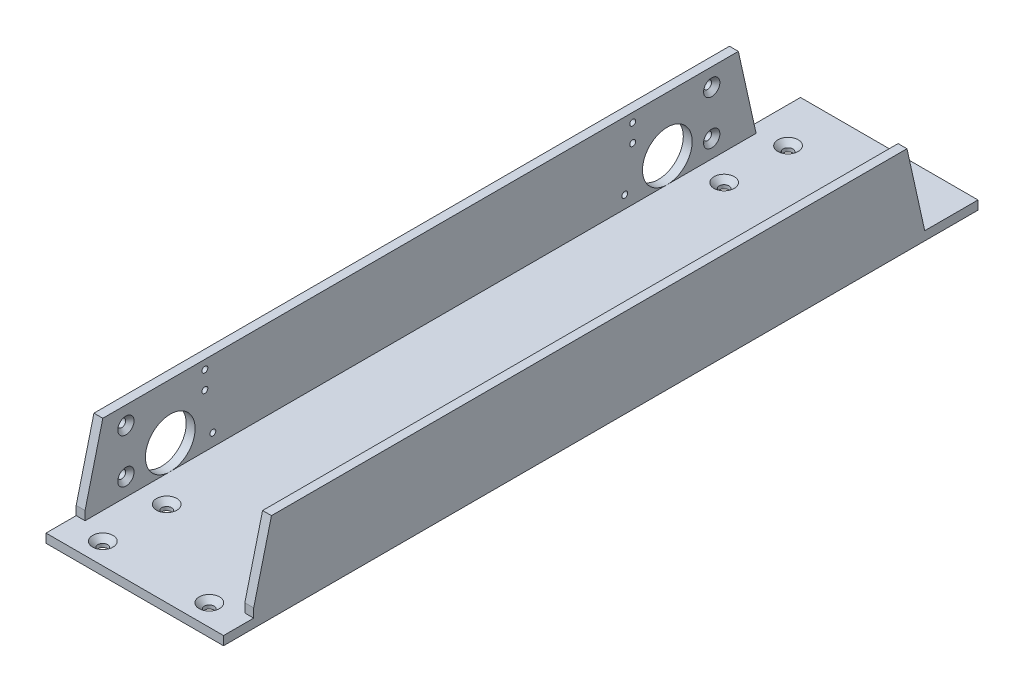
SolidWorks part; units mm, degrees
material "Д16Т ГОСТ 4784-74"
ref_plane "Спереди" through (0, 0, 0) normal (0, 0, 1) x (1, 0, 0)
ref_plane "Сверху" through (0, 0, 0) normal (0, 1, 0) x (1, 0, 0)
ref_plane "Справа" through (0, 0, 0) normal (1, 0, 0) x (0, 0, -1)
sketch "Эскиз1" plane through (0, 0, 0) normal (0, 0, 1) x (1, 0, 0)
  line L0 (0, 0) -> (0, 50)
  line L1 (0, 50) -> (5, 50)
  line L2 (5, 50) -> (5, 5)
  line L3 (5, 5) -> (95, 5)
  line L4 (95, 5) -> (95, 50)
  line L5 (95, 50) -> (100, 50)
  line L6 (100, 50) -> (100, 0)
  line L7 (100, 0) -> (0, 0)
  line L8 (5, 5) -> (5, 0) construction
  dimension "D1" = 100
  dimension "D2" = 50
  dimension "D3" = 5
extrude "Бобышка-Вытянуть1" add sketch "Эскиз1" along normal blind 400
hole_wizard "Зенковка для винта с потайной головкой и внутренним шестигранником M51" positions "Эскиз10" profile "Эскиз9" countersink size "M5" standard "DIN" end condition through all
sketch "Эскиз10" plane through (0, 5, 0) normal (0, 1, 0) x (-1, 0, 0)
  line L0 (-50, 400) -> (-50, 252.8897) construction
  line L1 (-95, 400) -> (-5, 400) construction
  line L3 (-10.9061, 375) -> (-70.1263, 375) construction
  line L4 (-5, 200) -> (-80, 200) construction
  line L5 (-5, 400) -> (-5, 0) construction
  line L7 (-10.9061, 25) -> (-70.1263, 25) construction
  line L8 (-50, 0) -> (-50, 147.1103) construction
  point P0 (-80, 393)
  point P1 (-20, 393)
  point P3 (-20, 357)
  point P5 (-80, 357)
  point P32 (-80, 43)
  point P33 (-20, 43)
  point P34 (-20, 7)
  point P35 (-80, 7)
  dimension "D1" = 60
  dimension "D2" = 25
  dimension "D3" = 36
sketch "Эскиз9" plane through (80, 5, 393) normal (1, 0, 0) x (0, 0, 1)
  line L0 (0, 0) -> (0, 5)
  line L1 (0, 5) -> (2.75, 5)
  line L2 (2.75, 5) -> (2.75, 2.985)
  line L3 (2.75, 2.985) -> (5.735, 0)
  line L5 (5.735, 0) -> (0, 0)
  line L6 (-2.75, 2.985) -> (-5.735, 0) construction
  line L11 (0, -6.35) -> (0, 107.95) construction
  dimension "Диаметр сквозного отверстия" = 5.5
  dimension "Глубина сквозного отверстия" = 5
  dimension "Диаметр передней зенковки" = 11.47
  dimension "Угол передней зенковки" = 90
hole_wizard "Отверстие обработанное метчиком M41" positions "Эскиз5" profile "Эскиз4" tap size "M4" standard "DIN"
sketch "Эскиз5" plane through (0, 0, 0) normal (-1, 0, 0) x (0, 0, 1)
  line L0 (400, 0) -> (0, 0) construction
  line L5 (200, 35.6515) -> (200, 0) construction
  line L6 (400, 0) -> (0, 0) construction
  point P0 (84, 12)
  point P1 (316, 12)
  dimension "D1" = 232
  dimension "D2" = 12
sketch "Эскиз4" plane through (0, 12, 84) normal (0, 1, 0) x (0, 0, 1)
  line L0 (0, 0) -> (0, 12.4914)
  line L1 (0, 12.4914) -> (1.65, 11.5)
  line L2 (1.65, 11.5) -> (1.65, 0.2165)
  line L3 (1.65, 0.2165) -> (2.025, 0)
  line L5 (2.025, 0) -> (0, 0)
  line L6 (-1.65, 0.2165) -> (-2.025, 0) construction
  line L10 (0, 12.4914) -> (-1.65, 11.5) construction
  line L11 (0, -6.35) -> (0, 107.95) construction
  dimension "Диаметр сверла" = 3.3
  dimension "Глубина сверла" = 11.5
  dimension "Диаметр передней зенковки" = 4.05
  dimension "Угол передней зенковки" = 120
  dimension "Угол заточки сверла" = 118
cosmetic thread "Отверстие резьбы1" parameters "D1"=5, "D2"=4
cosmetic thread "Отверстие резьбы2" parameters "D1"=5, "D2"=4
hole_wizard "Отверстие обработанное метчиком M42" positions "Эскиз7" profile "Эскиз6" tap size "M4" standard "DIN"
sketch "Эскиз7" plane through (0, 0, 0) normal (-1, 0, 0) x (0, 0, 1)
  line L0 (200, 44.8121) -> (200, 13.51) construction
  line L2 (400, 50) -> (0, 50) construction
  circle A0 centre (316, 12) radius 1.65 construction
  circle A1 centre (84, 12) radius 1.65 construction
  point P0 (320.5, 35)
  point P1 (320.5, 45)
  point P15 (79.5, 45)
  point P16 (79.5, 35)
  dimension "D1" = 241
  dimension "D2" = 10
  dimension "D3" = 5
sketch "Эскиз6" plane through (0, 35, 320.5) normal (0, 1, 0) x (0, 0, 1)
  line L0 (0, 0) -> (0, 12.4914)
  line L1 (0, 12.4914) -> (1.65, 11.5)
  line L2 (1.65, 11.5) -> (1.65, 0.2165)
  line L3 (1.65, 0.2165) -> (2.025, 0)
  line L5 (2.025, 0) -> (0, 0)
  line L6 (-1.65, 0.2165) -> (-2.025, 0) construction
  line L10 (0, 12.4914) -> (-1.65, 11.5) construction
  line L11 (0, -6.35) -> (0, 107.95) construction
  dimension "Диаметр сверла" = 3.3
  dimension "Глубина сверла" = 11.5
  dimension "Диаметр передней зенковки" = 4.05
  dimension "Угол передней зенковки" = 120
  dimension "Угол заточки сверла" = 118
cosmetic thread "Отверстие резьбы3" parameters "D1"=5, "D2"=4
cosmetic thread "Отверстие резьбы4" parameters "D1"=5, "D2"=4
cosmetic thread "Отверстие резьбы5" parameters "D1"=5, "D2"=4
cosmetic thread "Отверстие резьбы6" parameters "D1"=5, "D2"=4
sketch "Эскиз8" plane through (5, 0, 0) normal (1, 0, 0) x (0, 0, -1)
  line L0 (-400, 5) -> (0, 5) construction
  line L1 (-200, 43.2303) -> (-200, 13.468) construction
  circle A0 centre (-340, 19) radius 14
  circle A1 centre (-60, 19) radius 14
  circle A2 centre (-320.5, 35) radius 1.65 construction
  circle A3 centre (-79.5, 35) radius 1.65 construction
  dimension "D1" = 28
  dimension "D2" = 280
extrude "Вырез-Вытянуть2" cut sketch "Эскиз8" against normal blind 10
sketch "Эскиз3" plane through (0, 0, 400) normal (0, 0, 1) x (1, 0, 0)
  line L0 (95, 5) -> (5, 5)
  line L1 (95, 5) -> (5, 5)
  line L2 (95, 50) -> (95, 5)
  line L3 (95, 50) -> (95, 5)
  line L4 (100, 50) -> (95, 50)
  line L5 (100, 50) -> (95, 50)
  line L6 (5, 50) -> (0, 50)
  line L7 (5, 50) -> (0, 50)
  line L8 (5, 5) -> (5, 50)
  line L9 (5, 5) -> (5, 50)
  line L10 (100, 0) -> (100, 50)
  line L11 (100, 0) -> (100, 50)
  line L12 (0, 0) -> (100, 0)
  line L13 (0, 0) -> (100, 0)
  line L14 (0, 50) -> (0, 0)
  line L15 (0, 50) -> (0, 0)
extrude "Бобышка-Вытянуть2" add sketch "Эскиз3" along normal blind 10
sketch "Эскиз11" plane through (100, 0, 0) normal (1, 0, 0) x (0, 0, -1)
  line L0 (-410, 0) -> (-410, 50) construction
  line L1 (-410, 10) -> (-388, 10) construction
  line L2 (-410, 10) -> (-410, 5)
  line L3 (-405, 5) -> (-388, 5)
  line L4 (-388, 10) -> (-388, 5)
  line L5 (-410, 5) -> (0, 5) construction
  line L6 (-388, 10) -> (-378, 50)
  line L7 (-410, 50) -> (0, 50) construction
  line L8 (-378, 50) -> (-410, 50)
  line L9 (-410, 50) -> (-410, 10)
  line L10 (-410, 0) -> (0, 0) construction
  line L11 (0, 5) -> (-10, 5)
  line L12 (-410, 5) -> (-410, 0)
  line L13 (-410, 0) -> (-405, 0)
  line L14 (-405, 5) -> (-405, 0)
  line L15 (0, 0) -> (0, 50) construction
  line L16 (-10, 5) -> (-20, 50)
  line L17 (-20, 50) -> (0, 50)
  line L18 (0, 50) -> (0, 5)
  dimension "D1" = 22
  dimension "D2" = 5
  dimension "D3" = 32
  dimension "D4" = 5
  dimension "D5" = 10
  dimension "D6" = 20
extrude "Вырез-Вытянуть3" cut sketch "Эскиз11" against normal through all
sketch "Эскиз12" plane through (0, 0, 0) normal (0, 0, -1) x (-1, 0, 0)
  line L0 (0, 5) -> (0, 0) construction
  line L1 (-100, 0) -> (0, 0)
  line L2 (-100, 0) -> (-100, 5)
  line L3 (-100, 5) -> (0, 5)
  line L4 (0, 0) -> (0, 5)
  line L5 (-100, 5) -> (0, 5) construction
extrude "Бобышка-Вытянуть3" add sketch "Эскиз12" along normal blind 20
hole_wizard "Зенковка для винта с потайной головкой и внутренним шестигранником M41" positions "Эскиз16" profile "Эскиз15" countersink size "M4" standard "DIN"
sketch "Эскиз16" plane through (5, 0, 0) normal (1, 0, 0) x (0, 0, -1)
  line L0 (-200, 36.0065) -> (-200, 12.6603) construction
  line L2 (-365, 40) -> (-365, 15)
  line L4 (-405, 0) -> (20, 0) construction
  line L5 (-35, 40) -> (-35, 15)
  circle A2 centre (-340, 19) radius 14 construction
  circle A3 centre (-60, 19) radius 14 construction
  point P0 (-365, 40)
  point P1 (-365, 15)
  point P22 (-35, 15)
  point P23 (-35, 40)
  dimension "D1" = 25
  dimension "D2" = 15
  dimension "D3" = 330
sketch "Эскиз15" plane through (5, 40, 365) normal (0, 1, 0) x (0, 0, -1)
  line L0 (0, 0) -> (0, 5)
  line L1 (0, 5) -> (2.25, 5)
  line L2 (2.25, 5) -> (2.25, 2.34)
  line L3 (2.25, 2.34) -> (4.59, 0)
  line L5 (4.59, 0) -> (0, 0)
  line L6 (-2.25, 2.34) -> (-4.59, 0) construction
  line L11 (0, -6.35) -> (0, 107.95) construction
  dimension "Диаметр сквозного отверстия" = 4.5
  dimension "Глубина сквозного отверстия" = 5
  dimension "Диаметр передней зенковки" = 9.18
  dimension "Угол передней зенковки" = 90
